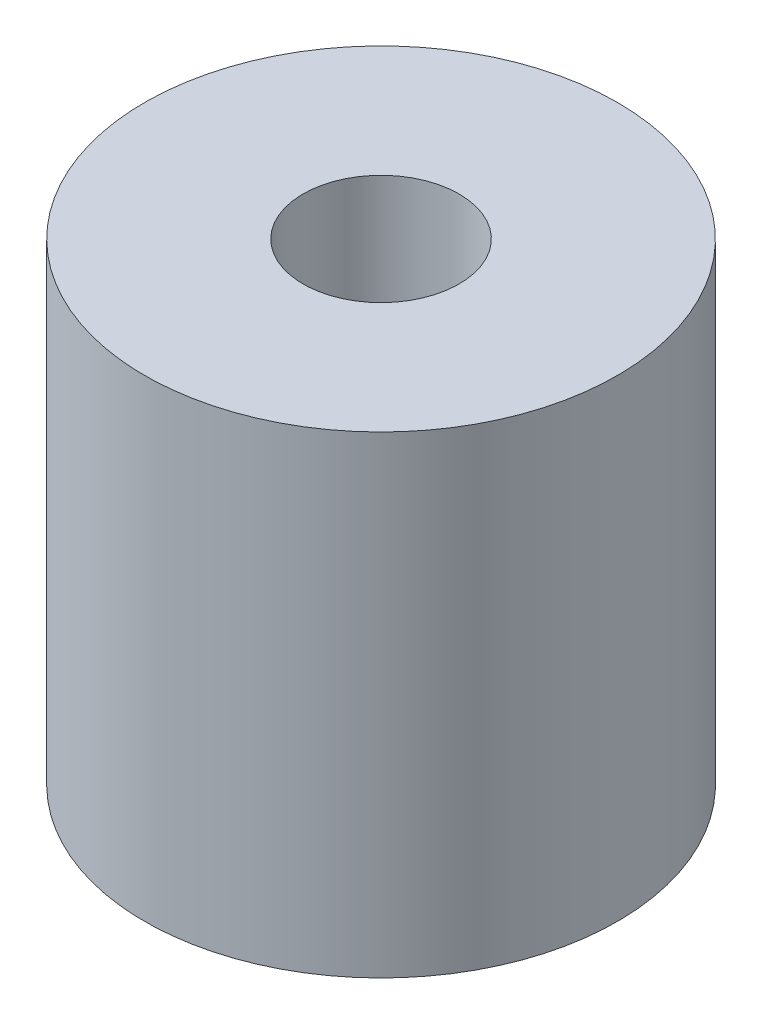
SolidWorks part; units mm, degrees
material "橡胶"
ref_plane "前视基准面" through (0, 0, 0) normal (0, 0, 1) x (1, 0, 0)
ref_plane "上视基准面" through (0, 0, 0) normal (0, 1, 0) x (1, 0, 0)
ref_plane "右视基准面" through (0, 0, 0) normal (1, 0, 0) x (0, 0, -1)
sketch "草图1" plane through (0, 0, 0) normal (0, 1, 0) x (1, 0, 0)
  circle A0 centre (0, 0) radius 5
  dimension "D1" = 10
extrude "凸台-拉伸1" add sketch "草图1" along normal mid plane 10
hole_wizard "M4 螺纹孔1" positions "草图3" profile "草图2" tap size "M4" standard "GB" end condition through all
sketch "草图3" plane through (0, 5, 0) normal (0, 1, 0) x (1, 0, 0)
  point P0 (0, 0)
cosmetic thread "孔螺蚊线1" parameters "D2"=4
sketch "草图2" plane through (0, 5, 0) normal (1, 0, 0) x (0, 0, 1)
  line L0 (0, 0) -> (0, 10)
  line L1 (0, 10) -> (1.65, 10)
  line L2 (1.65, 10) -> (1.65, 0)
  line L5 (1.65, 0) -> (0, 0)
  line L11 (0, -6.35) -> (0, 107.95) construction
  dimension "通孔螺纹孔钻头直径" = 3.3
  dimension "通孔螺纹孔钻头深度" = 10
sketch "草图4" plane through (0, -5, 0) normal (0, -1, 0) x (1, 0, 0)
  circle A0 centre (0, 0) radius 2
  dimension "D1" = 4
extrude "凸台-拉伸2" [suppressed] add sketch "草图4" along normal blind 10
move or copy body "实体-移动/复制1" bodies to move or copy 107
